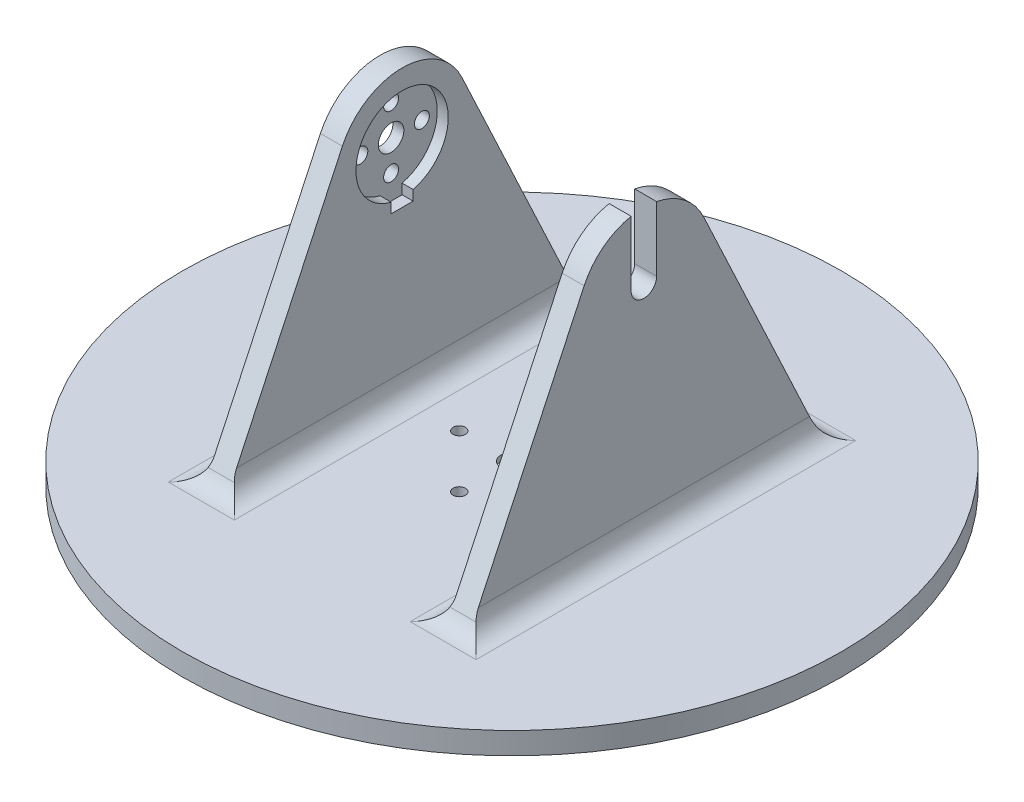
SolidWorks part; units mm, degrees
ref_plane "Front Plane" through (0, 0, 0) normal (0, 0, 1) x (1, 0, 0)
ref_plane "Top Plane" through (0, 0, 0) normal (0, 1, 0) x (1, 0, 0)
ref_plane "Right Plane" through (0, 0, 0) normal (1, 0, 0) x (0, 0, -1)
sketch "Sketch1" plane through (0, 0, 0) normal (0, 1, 0) x (1, 0, 0)
  circle A0 centre (0, 0) radius 75
  dimension "D1" = 150
extrude "Boss-Extrude1" add sketch "Sketch1" along normal blind 5 contours A0
sketch "Sketch2" plane through (0, 5, 0) normal (0, 1, 0) x (1, 0, 0)
  line L1 (-30, -40) -> (-25, -40)
  line L2 (-30, -40) -> (-30, 40)
  line L3 (-30, 40) -> (-25, 40)
  line L4 (-25, -40) -> (-25, 40)
  line L5 (-30, -40) -> (-25, 40) construction
  line L6 (-30, 40) -> (-25, -40) construction
  point P0 (-30, 0)
  dimension "D1" = 80
  dimension "D2" = 5
  dimension "D3" = 30
sketch "Sketch3" plane through (0, 5, 0) normal (0, 1, 0) x (1, 0, 0)
  line L1 (25, -40) -> (30, -40)
  line L2 (25, -40) -> (25, 40)
  line L3 (25, 40) -> (30, 40)
  line L4 (30, -40) -> (30, 40)
  line L5 (25, -40) -> (30, 40) construction
  line L6 (25, 40) -> (30, -40) construction
  dimension "D1" = 80
  dimension "D2" = 5
  dimension "D3" = 30
sketch3d "3DSketch1"
  line L0 (-25, 5, 40) -> (-25, 5, -40) construction
  line L2 (-30, 5, 40) -> (-25, 5, 40) construction
sketch "Sketch4" plane through (-25, 0, 0) normal (-1, 0, 0) x (0, 0, 1)
  line L0 (40, 5) -> (-40, 5) construction
  line L1 (-13.5822, 61.3658) -> (-40, 5)
  line L2 (13.5822, 61.3658) -> (40, 5)
  line L3 (-40, 5) -> (40, 5) construction
  line L4 (-40, 5) -> (40, 5)
  arc A0 (13.5822, 61.3658) -> (-13.5822, 61.3658) centre (0, 55) ccw
  dimension "D1" = 15
  dimension "D2" = 50
extrude "Boss-Extrude2" add sketch "Sketch4" along normal blind 5
sketch3d "3DSketch2"
  line L0 (25, 5, 40) -> (25, 5, -40) construction
  line L1 (25, 5, -40) -> (30, 5, -40) construction
sketch "Sketch5" plane through (25, 0, 0) normal (-1, 0, 0) x (0, 0, 1)
  line L0 (40, 5) -> (-40, 5) construction
  line L1 (13.5822, 61.3658) -> (40, 5)
  line L2 (40, 5) -> (-40, 5)
  line L3 (-13.5822, 61.3658) -> (-40, 5)
  arc A0 (13.5822, 61.3658) -> (-13.5822, 61.3658) centre (0, 55) ccw
  dimension "D1" = 15
  dimension "D2" = 50
extrude "Boss-Extrude3" add sketch "Sketch5" against normal blind 5
sketch "Sketch6" plane through (-30, 0, 0) normal (-1, 0, 0) x (0, 0, 1)
  circle A0 centre (0, 55) radius 1.5
  dimension "D1" = 3
extrude "Cut-Extrude1" cut sketch "Sketch6" against normal blind 5
sketch "Sketch7" plane through (-30, 0, 0) normal (-1, 0, 0) x (0, 0, 1)
  circle A0 centre (0, 55) radius 2.9
  dimension "D1" = 5.8
extrude "Cut-Extrude2" cut sketch "Sketch7" against normal blind 2.5
sketch "Sketch8" plane through (-30, 0, 0) normal (-1, 0, 0) x (0, 0, 1)
  circle A0 centre (0, 62.25) radius 0.6
  circle A1 centre (0, 55) radius 1.5 construction
  dimension "D1" = 1.2
  dimension "D2" = 7.25
extrude "Cut-Extrude3" cut sketch "Sketch8" against normal blind 5 contours A0
pattern_circular "CirPattern1" count 4 over 360 about axis through (0, 55, 0) along (1, 0, 0) of "Cut-Extrude3"
sketch "Sketch10" plane through (-30, 0, 0) normal (-1, 0, 0) x (0, 0, 1)
  circle A0 centre (0, 62) radius 1.7
  circle A1 centre (0, 55) radius 1.5 construction
  dimension "D1" = 3.4
  dimension "D2" = 7
extrude "Cut-Extrude4" cut sketch "Sketch10" against normal blind 3
pattern_circular "CirPattern2" count 4 over 360 about axis through (0, 55, 0) along (1, 0, 0) of "Cut-Extrude4"
sketch "Sketch11" plane through (0, 5, 0) normal (0, 1, 0) x (1, 0, 0)
  circle A0 centre (0, 0) radius 2.5
  dimension "D1" = 5
extrude "Cut-Extrude5" cut sketch "Sketch11" against normal blind 5
sketch "Sketch12" plane through (0, 5, 0) normal (0, 1, 0) x (1, 0, 0)
  circle A0 centre (0, 12) radius 1.4
  circle A1 centre (0, 0) radius 2.5 construction
  dimension "D1" = 2.8
  dimension "D2" = 12
extrude "Cut-Extrude6" cut sketch "Sketch12" against normal blind 5
pattern_circular "CirPattern3" count 4 over 360 about axis through (0, 0, 0) along (0, 1, 0) of "Cut-Extrude6"
sketch "Sketch13" plane through (0, 5, 0) normal (0, 1, 0) x (1, 0, 0)
  circle A0 centre (0, 12) radius 2.4883
sketch "Sketch14" plane through (0, 5, 0) normal (0, 1, 0) x (1, 0, 0)
  circle A0 centre (0, 0) radius 2.5
  dimension "D1" = 5
sketch "Sketch16" plane through (-25, 0, 0) normal (1, 0, 0) x (0, 0, -1)
  circle A0 centre (0, 55) radius 10.5
  dimension "D1" = 21
extrude "Cut-Extrude10" cut sketch "Sketch16" against normal blind 2.5 contours A0
sketch "Sketch18" plane through (30, 0, 0) normal (1, 0, 0) x (0, 0, -1)
  line L0 (-2.9, 55) -> (-2.9, 69.717)
  line L1 (2.9, 55) -> (2.9, 69.717)
  arc A0 (-2.9, 55) -> (2.9, 55) centre (0, 55) ccw
  arc A1 (13.5822, 61.3658) -> (-13.5822, 61.3658) centre (0, 55) ccw construction
  arc A2 (-2.9, 69.717) -> (2.9, 69.717) centre (0, 55) cw
  dimension "D1" = 5.8
extrude "Cut-Extrude11" cut sketch "Sketch18" against normal blind 5
fillet "Fillet1" radius 5 8 edges at (27.5, 5, 40) (27.5, 5, -40) (-27.5, 5, -40) (-27.5, 5, 40) (30, 5, 0) (25, 5, 0) (-25, 5, 0) (-30, 5, 0)
sketch "Sketch19" plane through (0, 0, 0) normal (0, -1, 0) x (-1, 0, 0)
  circle A0 centre (0, 0) radius 15.25
  dimension "D1" = 30.5
extrude "Cut-Extrude12" cut sketch "Sketch19" against normal blind 2
sketch "Sketch20" plane through (-25, 0, 0) normal (1, 0, 0) x (0, 0, -1)
  line L1 (-2.5, 46.5) -> (2.5, 46.5)
  line L2 (-2.5, 46.5) -> (-2.5, 42.5)
  line L3 (-2.5, 42.5) -> (2.5, 42.5)
  line L4 (2.5, 46.5) -> (2.5, 42.5)
  line L5 (-2.5, 46.5) -> (2.5, 42.5) construction
  line L6 (-2.5, 42.5) -> (2.5, 46.5) construction
  circle A0 centre (0, 55) radius 10.5 construction
  point P0 (0, 44.5)
  dimension "D1" = 5
  dimension "D2" = 4
extrude "Cut-Extrude13" cut sketch "Sketch20" against normal blind 2.5
sketch "Sketch21" plane through (0, 2, 0) normal (0, -1, 0) x (-1, 0, 0)
  circle A0 centre (0, 0) radius 6.5
  dimension "D1" = 13
extrude "Cut-Extrude14" cut sketch "Sketch21" against normal blind 1.75
